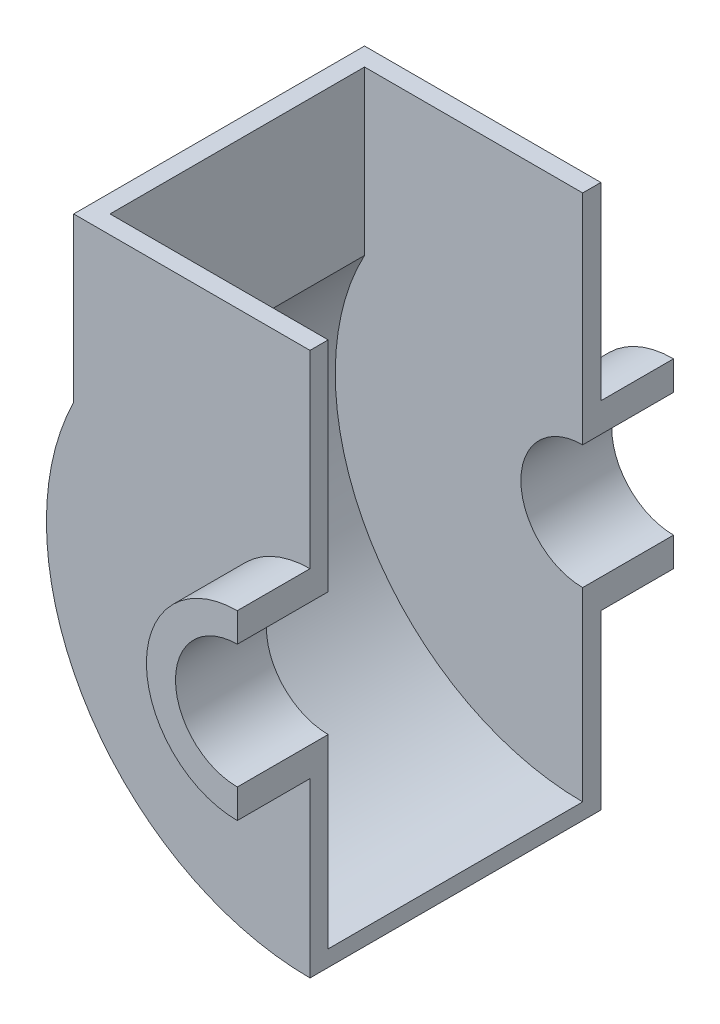
SolidWorks part; units mm, degrees
ref_plane "Front Plane" through (0, 0, 0) normal (0, 0, 1) x (1, 0, 0)
ref_plane "Top Plane" through (0, 0, 0) normal (0, 1, 0) x (1, 0, 0)
ref_plane "Right Plane" through (0, 0, 0) normal (1, 0, 0) x (0, 0, -1)
sketch "Sketch1" plane through (0, 0, 0) normal (0, 0, 1) x (1, 0, 0)
  line L0 (0, 25) -> (0, 17)
  line L1 (0, -17) -> (0, -25)
  arc A0 (0, 25) -> (0, -25) centre (0, 0) ccw
  arc A1 (0, 17) -> (0, -17) centre (0, 0) ccw
  dimension "D1" = 50
  dimension "D2" = 34
extrude "Boss-Extrude1" add sketch "Sketch1" along normal blind 20 and the other way blind 5
sketch "Sketch2" plane through (0, 0, 0) normal (0, 0, 1) x (1, 0, 0)
  line L0 (0, -25) -> (0, -72.5)
  line L1 (0, 25) -> (0, 77)
  line L2 (0, 77) -> (-65, 77)
  line L3 (-65, 77) -> (-65, 32.1131)
  arc A0 (-65, 32.1131) -> (0, -72.5) centre (0, 0) ccw
  arc A1 (0, 25) -> (0, -25) centre (0, 0) ccw
  dimension "D1" = 145
  dimension "D2" = 52
  dimension "D3" = 65
extrude "Boss-Extrude2" add sketch "Sketch2" against normal blind 5 contours A1 L1 L2 L3 A0 L0
ref_plane "Plane1" through (0, 0, -40) normal (0, 0, 1) x (1, 0, 0)
mirror "Mirror1" about plane through (0, 0, -40) normal (0, 0, 1) of bodies 102
sketch "Sketch3" plane through (0, 0, -5) normal (0, 0, -1) x (-1, 0, 0)
  line L0 (65, 32.1131) -> (65, 77)
  line L1 (65, 77) -> (60, 77)
  line L2 (0, 77) -> (65, 77) construction
  line L3 (60, 77) -> (60, 32.1131)
  line L4 (0, -68.0533) -> (0, -72.5)
  arc A0 (0, -72.5) -> (65, 32.1131) centre (0, 0) ccw
  arc A1 (0, -68.0533) -> (60, 32.1131) centre (0, 0) ccw
  dimension "D1" = 5
extrude "Boss-Extrude3" add sketch "Sketch3" along normal up to surface (70 mm away)
